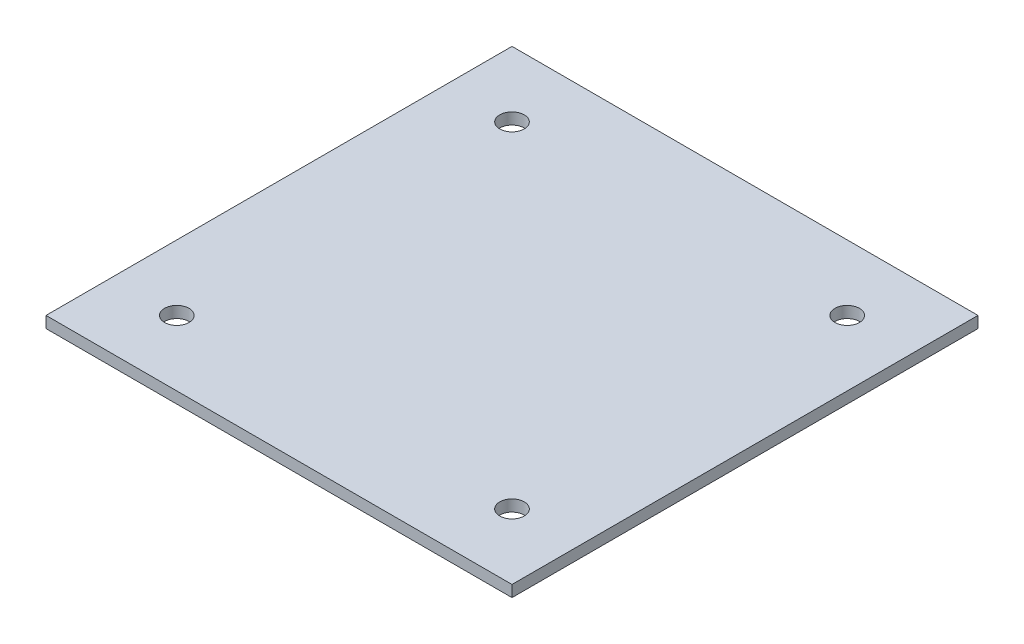
SolidWorks part; units mm, degrees
ref_plane "Front Plane" through (0, 0, 0) normal (0, 0, 1) x (1, 0, 0)
ref_plane "Top Plane" through (0, 0, 0) normal (0, 1, 0) x (1, 0, 0)
ref_plane "Right Plane" through (0, 0, 0) normal (1, 0, 0) x (0, 0, -1)
sketch "Sketch1" plane through (0, 0, 0) normal (0, 1, 0) x (1, 0, 0)
  line L0 (-1000, 0) -> (49000, 0) construction
  line L1 (0, -1000) -> (0, 49000) construction
  line L2 (707.1069, -707.1069) -> (-34648.2322, 34648.2322) construction
  line L3 (-707.1068, -707.1068) -> (34648.2323, 34648.2323) construction
  line L4 (716.0871, -698.1266) -> (0, 17.9605) construction
  line L5 (-698.1265, -716.087) -> (34657.2125, 34639.252) construction
  line L6 (698.1266, -716.0871) -> (-34657.2125, 34639.2519) construction
  line L7 (-716.087, -698.1265) -> (0, 17.9605) construction
  line L8 (-733.6258, -670.2104) -> (-31.7077, 31.7077) construction
  line L9 (733.9751, -670.5597) -> (22.7274, 40.6879) construction
  line L11 (716.0871, -698.1266) -> (-34639.2519, 34657.2125) construction
  line L13 (-716.087, -698.1265) -> (34639.252, 34657.2125) construction
  line L14 (-12.5, -12.5) -> (12.5, -12.5)
  line L15 (-12.5, -12.5) -> (-12.5, 12.5)
  line L16 (-12.5, 12.5) -> (12.5, 12.5)
  line L17 (12.5, -12.5) -> (12.5, 12.5)
  line L18 (-12.5, -12.5) -> (12.5, 12.5) construction
  line L19 (-12.5, 12.5) -> (12.5, -12.5) construction
  line L42 (-28.5, -28.5) -> (28.5, -28.5)
  line L43 (-28.5, -28.5) -> (-28.5, 28.5)
  line L44 (-28.5, 28.5) -> (28.5, 28.5)
  line L45 (28.5, -28.5) -> (28.5, 28.5)
  line L46 (-28.5, -28.5) -> (28.5, 28.5) construction
  line L47 (-28.5, 28.5) -> (28.5, -28.5) construction
  circle A0 centre (-20.5, 20.5) radius 1.5
  circle A1 centre (-20.5, -20.5) radius 1.5
  circle A2 centre (20.5, -20.5) radius 1.5
  circle A3 centre (20.5, 20.5) radius 1.5
  circle A48 centre (0, 0) radius 6.1441 construction
  point P46 (0, 0)
  point P60 (0, 0)
  point P75 (-0.048, -0.2069)
  point P120 (0, 0)
  dimension "D1" = 12.7
  dimension "D2" = 12.7
extrude "Boss-Extrude1" add sketch "Sketch1" along normal blind 1.397 contours L42 L45 L44 L43 A1 A0 L17 L14 L15 L16 A2 A3 | L14 L17 L16 L15
